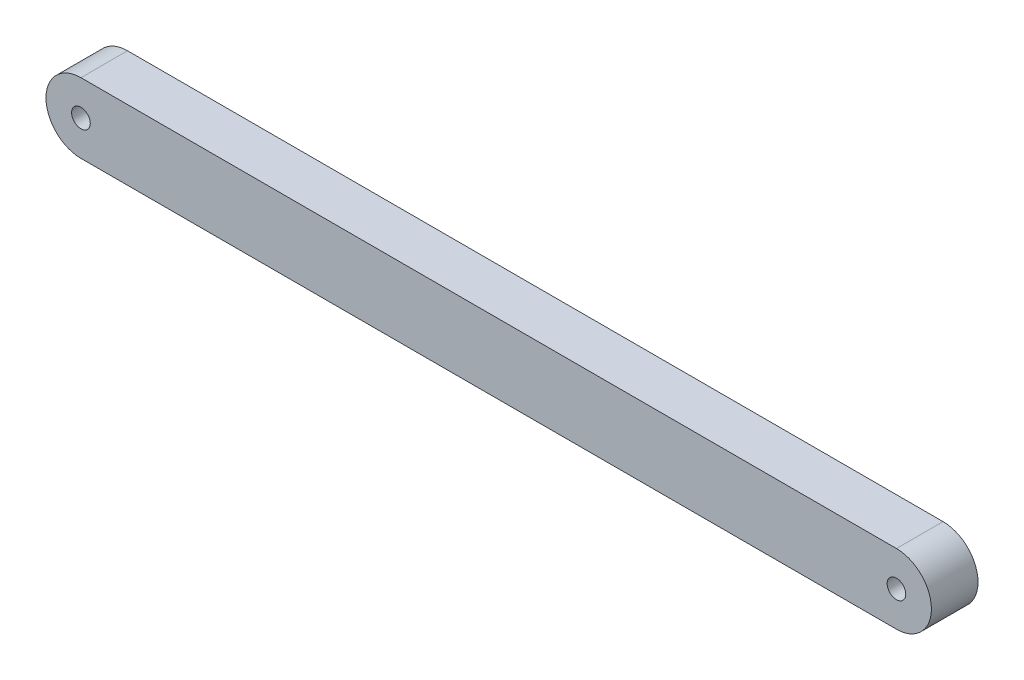
SolidWorks part; units mm, degrees
ref_plane "前视基准面" through (0, 0, 0) normal (0, 0, 1) x (1, 0, 0)
ref_plane "上视基准面" through (0, 0, 0) normal (0, 1, 0) x (1, 0, 0)
ref_plane "右视基准面" through (0, 0, 0) normal (1, 0, 0) x (0, 0, -1)
other "Configuration Table"
sketch "草图1" plane through (0, 0, 0) normal (0, 0, 1) x (1, 0, 0)
  line L0 (0, 0) -> (341.9784, 0) construction
  line L1 (0, -15) -> (350, -15)
  line L2 (0, 15) -> (350, 15)
  arc A0 (0, 15) -> (0, -15) centre (0, 0) ccw
  arc A1 (350, -15) -> (350, 15) centre (350, 0) ccw
extrude "凸台-拉伸1" add sketch "草图1" along normal blind 20
sketch "草图2" plane through (0, 0, 0) normal (0, 0, 1) x (1, 0, 0)
  circle A0 centre (0, 0) radius 4
  circle A1 centre (350, 0) radius 4
extrude "切除-拉伸1" cut sketch "草图2" along normal blind 20
